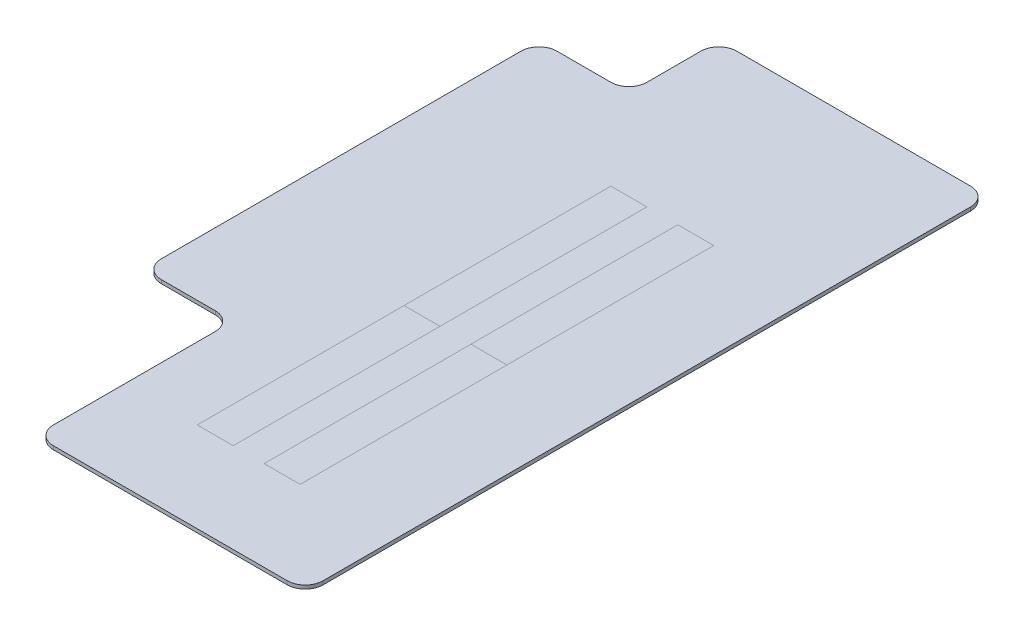
SolidWorks part; units mm, degrees
material "1.0116 (S235J2G3)"
ref_plane "Front Plane" through (0, 0, 0) normal (0, 0, 1) x (1, 0, 0)
ref_plane "Top Plane" through (0, 0, 0) normal (0, 1, 0) x (1, 0, 0)
ref_plane "Right Plane" through (0, 0, 0) normal (1, 0, 0) x (0, 0, -1)
sketch "Sketch2" plane through (0, 0, 0) normal (0, 1, 0) x (1, 0, 0)
  line L0 (-1000, 1600) -> (-1000, 600)
  line L1 (-950, 550) -> (-800, 550)
  line L2 (-750, 500) -> (-750, 50)
  line L3 (-700, 0) -> (-50, 0)
  line L4 (0, 50) -> (0, 1850)
  line L5 (-50, 1900) -> (-700, 1900)
  line L6 (-750, 1850) -> (-750, 1700)
  line L7 (-800, 1650) -> (-950, 1650)
  arc A0 (-50, 0) -> (0, 50) centre (-50, 50) ccw
  arc A1 (-750, 50) -> (-700, 0) centre (-700, 50) ccw
  arc A2 (-800, 550) -> (-750, 500) centre (-800, 500) cw
  arc A3 (-1000, 600) -> (-950, 550) centre (-950, 600) ccw
  arc A4 (-750, 1700) -> (-800, 1650) centre (-800, 1700) cw
  arc A5 (-1000, 1600) -> (-950, 1650) centre (-950, 1600) cw
  arc A6 (-700, 1900) -> (-750, 1850) centre (-700, 1850) ccw
  arc A7 (0, 1850) -> (-50, 1900) centre (-50, 1850) ccw
  point P11 (0, 0)
  point P16 (-750, 550)
  point P19 (-1000, 550)
  point P22 (-750, 1650)
  point P25 (-1000, 1650)
  point P28 (-750, 1900)
  dimension "D9" = 50
  dimension "D1" = 1000
  dimension "D2" = 1100
  dimension "D3" = 250
  dimension "D4" = 250
  dimension "D5" = 550
  dimension "D6" = 250
  dimension "D7" = 0
  dimension "D8" = 0
extrude "Boss-Extrude1" add sketch "Sketch2" along normal blind 10
sketch "Sketch3" plane through (0, 10, 0) normal (0, 1, 0) x (1, 0, 0)
  line L0 (-450, 1400) -> (-450, 250)
  line L1 (-450, 250) -> (-550, 250)
  line L2 (-550, 250) -> (-550, 1400)
  line L3 (-550, 1400) -> (-450, 1400)
  line L4 (-364, 250) -> (-364, 1400)
  line L5 (-364, 1400) -> (-264, 1400)
  line L6 (-264, 1400) -> (-264, 250)
  line L7 (-264, 250) -> (-364, 250)
  line L8 (-700, 0) -> (-50, 0) construction
  line L9 (-750, 500) -> (-750, 50) construction
  line L10 (-550, 825) -> (-450, 825)
  line L11 (-364, 825) -> (-264, 825)
  point P10 (-314, 250)
  dimension "D1" = 1150
  dimension "D2" = 1150
  dimension "D3" = 100
  dimension "D4" = 86
  dimension "D5" = 100
  dimension "D6" = 250
  dimension "D7" = 200
  dimension "D8" = 250
split line "Split Line1"
sketch "Sketch5" plane through (0, 0, 0) normal (0, -1, 0) x (1, 0, 0)
  line L0 (-960, -550) -> (-960, -1650)
  line L1 (-950, -550) -> (-800, -550) construction
  line L2 (-800, -1650) -> (-950, -1650) construction
  line L3 (-960, -1650) -> (-880, -1650)
  line L4 (-880, -1650) -> (-880, -550)
  line L5 (-1000, -1600) -> (-1000, -600) construction
  line L6 (-750, -434.7223) -> (-750, -342.3463)
  line L7 (-750, -500) -> (-750, -50) construction
  line L8 (-750, -342.3463) -> (0, -775.359)
  line L9 (0, -50) -> (0, -1850) construction
  line L10 (0, -775.359) -> (0, -867.735)
  line L11 (0, -867.735) -> (-750, -434.7223)
  line L13 (-700, 0) -> (-50, 0) construction
  line L24 (-750, -1775.2777) -> (0, -1342.265)
  line L25 (-750, -1850) -> (-750, -1700) construction
  line L26 (0, -1342.265) -> (0, -1434.641)
  line L27 (0, -1434.641) -> (-750, -1867.6537)
  line L28 (-750, -1867.6537) -> (-750, -1775.2777)
  line L29 (-50, -1900) -> (-700, -1900) construction
  dimension "D1" = 40
  dimension "D2" = 80
  dimension "D3" = 80
  dimension "D4" = 30
  dimension "D5" = 120
  dimension "D6" = 557.735
  dimension "D7" = 80
  dimension "D8" = 867.735
split line "Split Line2"
